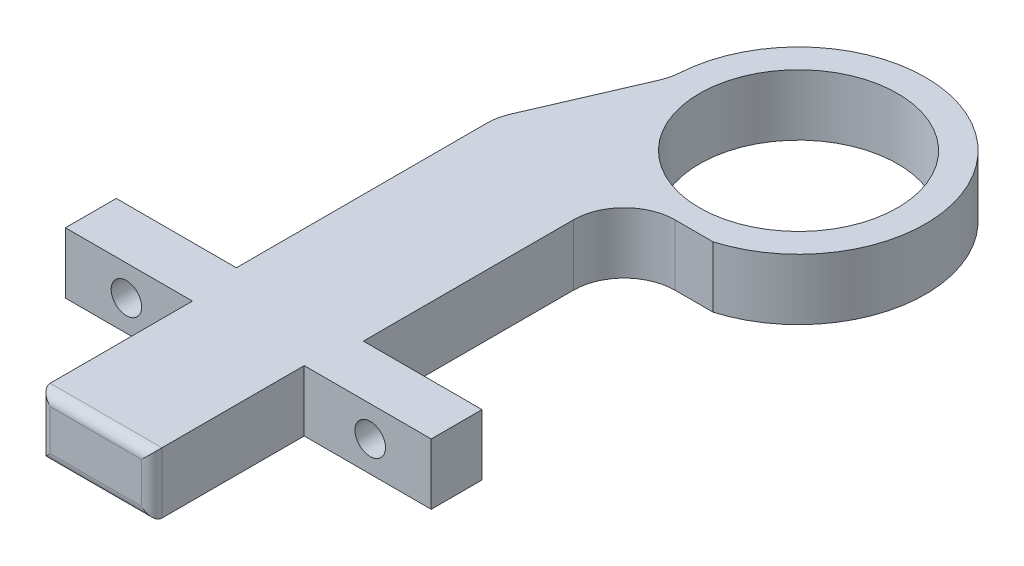
SolidWorks part; units mm, degrees
ref_plane "Alzado" through (0, 0, 0) normal (0, 0, 1) x (1, 0, 0)
ref_plane "Planta" through (0, 0, 0) normal (0, 1, 0) x (1, 0, 0)
ref_plane "Vista lateral" through (0, 0, 0) normal (1, 0, 0) x (0, 0, -1)
sketch "Croquis1" plane through (0, 0, 0) normal (0, 1, 0) x (1, 0, 0)
  line L0 (-12.5, 0) -> (-53.5222, 0) construction
  line L1 (0, 0) -> (-12.5, 21.6506) construction
  line L2 (-29.7673, 10.6211) -> (-25.3747, 20.7837)
  line L3 (-24, -36) -> (-24, -21) construction
  line L4 (-30.1777, -21) -> (-17.6777, -21)
  line L8 (-29.5, -21) -> (-18.5, -21)
  line L9 (-29.5, -21) -> (-29.5, -36)
  line L10 (-29.5, -36) -> (-18.5, -36)
  line L11 (-18.5, -21) -> (-18.5, -36)
  line L12 (-42, -16) -> (-27, -16) construction
  line L13 (-10.5, -16) -> (-6, -16) construction
  line L14 (-42, -16) -> (-27, -16)
  line L15 (-42, -16) -> (-42, -21)
  line L16 (-42, -21) -> (-30.1777, -21)
  line L18 (-6, -16) -> (-10.5, -16)
  line L19 (-6, -16) -> (-6, -21)
  line L20 (-6, -21) -> (-17.6777, -21)
  line L21 (-17.6777, -16) -> (-30.1777, -16)
  line L22 (-17.6777, -16) -> (-17.6777, 4.6717)
  line L23 (-17.6777, 9.6717) -> (-30.1777, 9.6717)
  line L24 (-30.1777, -16) -> (-30.1777, 8.6374)
  line L25 (-8.9286, 9.6717) -> (-12.6777, 9.6717)
  line L26 (-10.5, -16) -> (-17.6777, -16)
  arc A1 (-8.9286, 9.6717) -> (-24.9745, 22.4484) centre (-12.5, 21.6506) ccw
  circle A2 centre (-12.5, 21.6506) radius 9.75
  arc A6 (-30.1777, 8.6374) -> (-29.7673, 10.6211) centre (-25.1777, 8.6374) cw
  arc A7 (-24.9745, 22.4484) -> (-25.3747, 20.7837) centre (-29.9643, 22.7675) cw
  arc A8 (-17.6777, 4.6717) -> (-12.6777, 9.6717) centre (-12.6777, 4.6717) cw
  point P31 (-25, 21.6506)
  dimension "D3" = 25
  dimension "D4" = 5
  dimension "D5" = 19.5
  dimension "D6" = 21
  dimension "D1" = 25
  dimension "D2" = 60
  dimension "D7" = 11
  dimension "D8" = 15
  dimension "D9" = 24
  dimension "D10" = 5
  dimension "D11" = 18
  dimension "D12" = 18
extrude "Saliente-Extruir1" add sketch "Croquis1" along normal blind 6
sketch "Croquis2" plane through (0, 0, 21) normal (0, 0, 1) x (1, 0, 0)
  line L0 (-42, 3) -> (-6, 3) construction
  line L1 (-42, 6) -> (-42, 0) construction
  line L2 (-6, 6) -> (-6, 0) construction
  line L3 (-24, 6) -> (-24, 0) construction
  line L4 (-29.5, 6) -> (-18.5, 6) construction
  line L5 (-29.5, 0) -> (-18.5, 0) construction
  circle A0 centre (-36, 3) radius 1.5
  circle A1 centre (-12, 3) radius 1.5
  dimension "D3" = 3
  dimension "D4" = 3
  dimension "D1" = 12
  dimension "D2" = 12
extrude "Cortar-Extruir1" cut sketch "Croquis2" against normal blind 6
fillet "Redondeo1" radius 1 4 edges at (-29.5, 3, 36) (-18.5, 3, 36) (-24, 6, 36) (-24, 0, 36)
